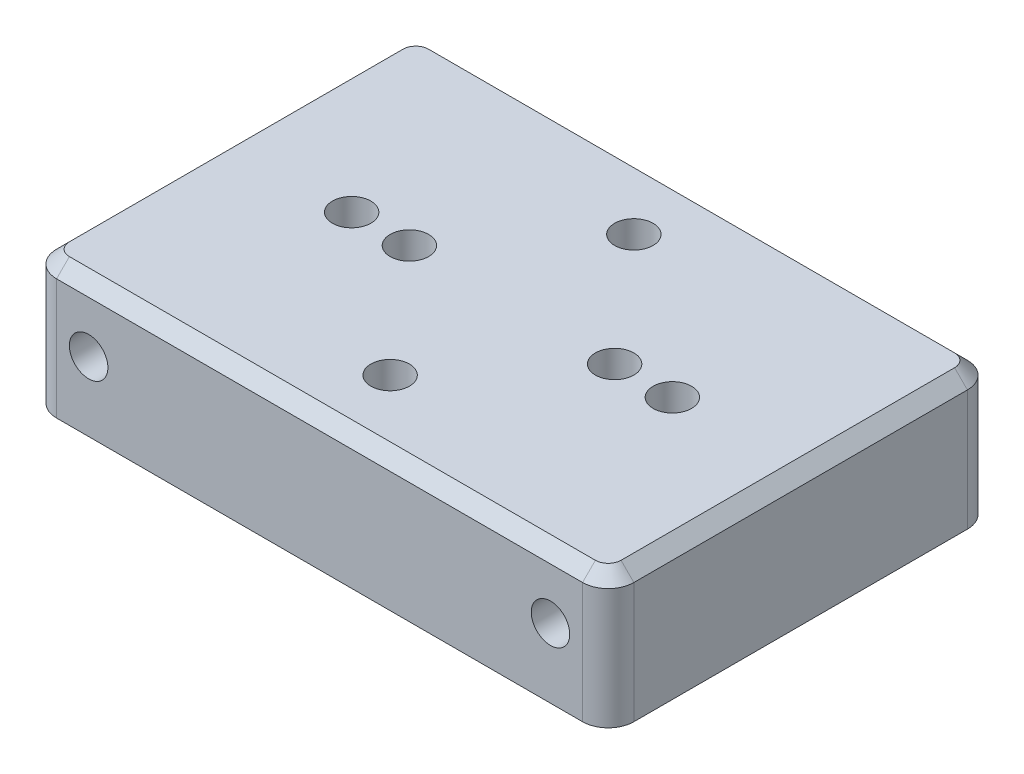
SolidWorks part; units mm, degrees
ref_plane "정면" through (0, 0, 0) normal (0, 0, 1) x (1, 0, 0)
ref_plane "윗면" through (0, 0, 0) normal (0, 1, 0) x (1, 0, 0)
ref_plane "우측면" through (0, 0, 0) normal (1, 0, 0) x (0, 0, -1)
sketch "스케치1" plane through (0, 0, 0) normal (0, 1, 0) x (1, 0, 0)
  line L1 (-22.5, -15) -> (22.5, -15)
  line L2 (-22.5, -15) -> (-22.5, 15)
  line L3 (-22.5, 15) -> (22.5, 15)
  line L4 (22.5, -15) -> (22.5, 15)
  line L5 (-22.5, -15) -> (22.5, 15) construction
  line L6 (-22.5, 15) -> (22.5, -15) construction
  circle A0 centre (0, 0) radius 8 construction
  circle A1 centre (-8, 0) radius 1.5
  circle A2 centre (0, 0) radius 9.5 construction
  circle A3 centre (0, 0) radius 12.5 construction
  circle A4 centre (8, 0) radius 1.5
  circle A5 centre (0, 9.5) radius 1.5
  circle A6 centre (0, -9.5) radius 1.5
  circle A7 centre (-12.5, 0) radius 1.5
  circle A8 centre (12.5, 0) radius 1.5
  point P0 (0, 0)
  dimension "D1" = 3
  dimension "D2" = 16
  dimension "D4" = 19
  dimension "D5" = 25
  dimension "D3" = 30
  dimension "D6" = 45
extrude "보스-돌출1" add sketch "스케치1" along normal blind 10
sketch "스케치2" plane through (0, 0, 15) normal (0, 0, 1) x (1, 0, 0)
  line L0 (0, 10) -> (0, 0) construction
  line L1 (-22.5, 10) -> (22.5, 10) construction
  line L2 (-22.5, 5) -> (22.5, 5) construction
  line L3 (-22.5, 10) -> (-22.5, 0) construction
  line L4 (22.5, 10) -> (22.5, 0) construction
  circle A0 centre (-18, 5) radius 1.5
  circle A1 centre (18, 5) radius 1.5
  dimension "D1" = 3
  dimension "D2" = 36
extrude "컷-돌출1" cut sketch "스케치2" against normal through all
fillet "필렛1" radius 2 4 edges at (22.5, 5, 15) (22.5, 5, -15) (-22.5, 5, -15) (-22.5, 5, 15)
chamfer "모따기2" distance 1 angle 45 8 edges at (21.9142, 10, -14.4142) (0, 10, -15) (22.5, 10, 0) (-21.9142, 10, -14.4142) (21.9142, 10, 14.4142) (-22.5, 10, 0) (0, 10, 15) (-21.9142, 10, 14.4142)
sketch "스케치3" plane through (0, 0, 0) normal (0, -1, 0) x (1, 0, 0)
  line L0 (-22.5, 0) -> (22.5, 0) construction
  line L1 (-22.5, -13) -> (-22.5, 13) construction
  line L2 (22.5, 13) -> (22.5, -13) construction
  line L3 (0, 15) -> (0, -15) construction
  line L4 (-20.5, 15) -> (20.5, 15) construction
  line L5 (20.5, -15) -> (-20.5, -15) construction
  circle A0 centre (-18, 0) radius 1.5
  circle A1 centre (18, 0) radius 1.5
  dimension "D1" = 3
  dimension "D2" = 36
extrude "컷-돌출2" cut sketch "스케치3" against normal blind 5
sketch "스케치4" plane through (0, 0, 0) normal (0, -1, 0) x (1, 0, 0)
  line L4 (22.5, -13) -> (22.5, 13)
  line L5 (20.5, 15) -> (-20.5, 15)
  line L6 (-22.5, 13) -> (-22.5, -13)
  line L7 (-20.5, -15) -> (20.5, -15)
  line L8 (22.5, -13) -> (22.5, 13)
  line L9 (20.5, 15) -> (-20.5, 15)
  line L10 (-22.5, 13) -> (-22.5, -13)
  line L11 (-20.5, -15) -> (20.5, -15)
  circle A1 centre (-18, 0) radius 1.5
  circle A2 centre (-18, 0) radius 1.5
  circle A3 centre (-12.5, 0) radius 1.5
  circle A4 centre (-12.5, 0) radius 1.5
  circle A5 centre (-8, 0) radius 1.5
  circle A6 centre (-8, 0) radius 1.5
  circle A7 centre (0, -9.5) radius 1.5
  circle A8 centre (0, -9.5) radius 1.5
  circle A9 centre (8, 0) radius 1.5
  circle A10 centre (8, 0) radius 1.5
  circle A11 centre (12.5, 0) radius 1.5
  circle A12 centre (12.5, 0) radius 1.5
  circle A13 centre (0, 9.5) radius 1.5
  circle A14 centre (0, 9.5) radius 1.5
  circle A15 centre (18, 0) radius 1.5
  circle A16 centre (18, 0) radius 1.5
  arc A20 (22.5, 13) -> (20.5, 15) centre (20.5, 13) ccw
  arc A21 (-20.5, 15) -> (-22.5, 13) centre (-20.5, 13) ccw
  arc A22 (-22.5, -13) -> (-20.5, -15) centre (-20.5, -13) ccw
  arc A23 (20.5, -15) -> (22.5, -13) centre (20.5, -13) ccw
  arc A24 (22.5, 13) -> (20.5, 15) centre (20.5, 13) ccw
  arc A25 (-20.5, 15) -> (-22.5, 13) centre (-20.5, 13) ccw
  arc A26 (-22.5, -13) -> (-20.5, -15) centre (-20.5, -13) ccw
  arc A27 (20.5, -15) -> (22.5, -13) centre (20.5, -13) ccw
  dimension "D1" = 0
  dimension "D2" = 0
  dimension "D3" = 0
  dimension "D4" = 0
  dimension "D5" = 0
  dimension "D6" = 0
  dimension "D7" = 0
  dimension "D8" = 0
  dimension "D9" = 0
extrude "보스-돌출2" add sketch "스케치4" along normal blind 0.4
